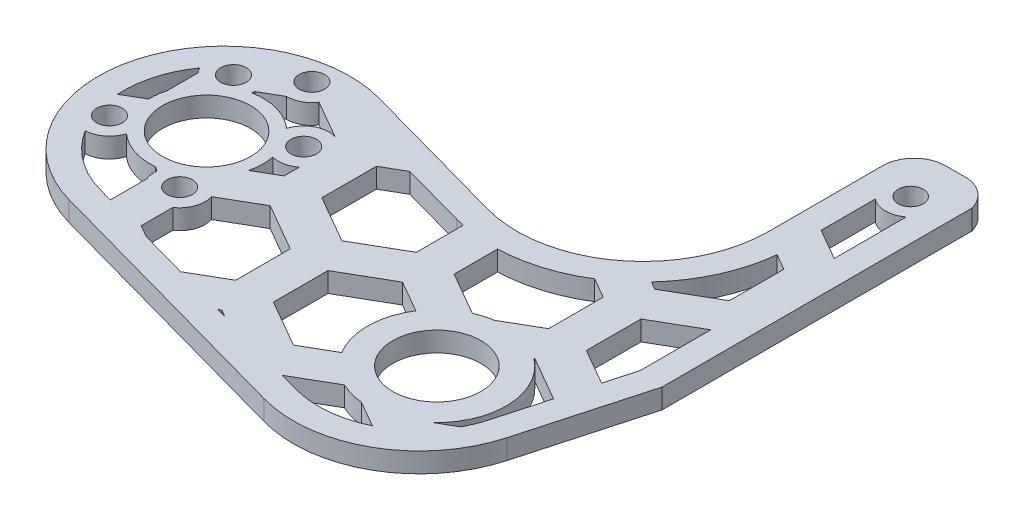
SolidWorks part; units mm, degrees
ref_plane "Front Plane" through (0, 0, 0) normal (0, 0, 1) x (1, 0, 0)
ref_plane "Top Plane" through (0, 0, 0) normal (0, 1, 0) x (1, 0, 0)
ref_plane "Right Plane" through (0, 0, 0) normal (1, 0, 0) x (0, 0, -1)
sketch "Sketch1" plane through (0, 0, 0) normal (0, 1, 0) x (1, 0, 0)
  line L12 (51.0281, 31.393) -> (48.107, 31.393)
  line L13 (43.107, 26.393) -> (43.107, 8.3528)
  line L14 (17.7622, -10.9198) -> (-6.126, -4.295)
  line L15 (-16.8156, -42.8402) -> (26.066, -54.7323)
  line L16 (50.6833, -40.8045) -> (56.0281, -21.5319)
  line L17 (56.0281, -21.5319) -> (56.0281, 26.393)
  circle A2 centre (35.2653, -36.5287) radius 7
  circle A4 centre (-15.3253, -22.4986) radius 7
  circle A6 centre (-5.4784, -16.9275) radius 2.025
  circle A8 centre (-9.7542, -32.3456) radius 2.025
  circle A10 centre (-25.1723, -28.0698) radius 2.025
  circle A12 centre (-20.8965, -12.6517) radius 2.025
  circle A14 centre (-13.7258, -7.3761) radius 2.025
  circle A16 centre (49.5676, 24.393) radius 2.05
  arc A28 (48.107, 31.393) -> (43.107, 26.393) centre (48.107, 26.393) ccw
  arc A29 (17.7622, -10.9198) -> (43.107, 8.3528) centre (23.107, 8.3528) ccw
  arc A30 (-6.126, -4.295) -> (-30.7434, -18.2228) centre (-11.4708, -23.5676) ccw
  arc A31 (-30.7434, -18.2228) -> (-16.8156, -42.8402) centre (-11.4708, -23.5676) ccw
  arc A32 (26.066, -54.7323) -> (50.6833, -40.8045) centre (31.4107, -35.4597) ccw
  arc A33 (56.0281, 26.393) -> (51.0281, 31.393) centre (51.0281, 26.393) ccw
extrude "Boss-Extrude1" add sketch "Sketch1" along normal blind 3.15
sketch "Sketch2" plane through (0, 3.15, 0) normal (0, 1, 0) x (1, 0, 0)
  line L0 (56.0281, -21.5319) -> (56.0281, 26.393) construction
  line L1 (0, 8.6603) -> (-7.5, 4.3301)
  line L2 (-7.5, 4.3301) -> (-7.5, -4.3301)
  line L3 (-7.5, -4.3301) -> (0, -8.6603)
  line L4 (0, -8.6603) -> (7.5, -4.3301)
  line L5 (7.5, -4.3301) -> (7.5, 4.3301)
  line L6 (7.5, 4.3301) -> (0, 8.6603)
  line L7 (21, 8.6603) -> (13.5, 4.3301)
  line L8 (13.5, 4.3301) -> (13.5, -4.3301)
  line L9 (13.5, -4.3301) -> (21, -8.6603)
  line L10 (21, -8.6603) -> (28.5, -4.3301)
  line L11 (28.5, -4.3301) -> (28.5, 4.3301)
  line L12 (28.5, 4.3301) -> (21, 8.6603)
  line L19 (10.5, -9.5263) -> (3, -13.8564)
  line L20 (3, -13.8564) -> (3, -22.5167)
  line L21 (3, -22.5167) -> (10.5, -26.8468)
  line L22 (10.5, -26.8468) -> (18, -22.5167)
  line L23 (18, -22.5167) -> (18, -13.8564)
  line L24 (18, -13.8564) -> (10.5, -9.5263)
  line L25 (31.5, -9.5263) -> (24, -13.8564)
  line L26 (24, -13.8564) -> (24, -22.5167)
  line L27 (24, -22.5167) -> (31.5, -26.8468)
  line L28 (31.5, -26.8468) -> (39, -22.5167)
  line L29 (39, -22.5167) -> (39, -13.8564)
  line L30 (39, -13.8564) -> (31.5, -9.5263)
  line L31 (10.5, -9.5263) -> (31.5, -9.5263) construction
  line L32 (52.5, -9.5263) -> (45, -13.8564)
  line L33 (45, -13.8564) -> (45, -22.5167)
  line L34 (45, -22.5167) -> (52.5, -26.8468)
  line L35 (52.5, -26.8468) -> (60, -22.5167)
  line L36 (60, -22.5167) -> (60, -13.8564)
  line L37 (60, -13.8564) -> (52.5, -9.5263)
  line L38 (42, 8.6603) -> (34.5, 4.3301)
  line L39 (34.5, 4.3301) -> (34.5, -4.3301)
  line L40 (34.5, -4.3301) -> (42, -8.6603)
  line L41 (42, -8.6603) -> (49.5, -4.3301)
  line L42 (49.5, -4.3301) -> (49.5, 4.3301)
  line L43 (49.5, 4.3301) -> (42, 8.6603)
  line L44 (63, 8.6603) -> (55.5, 4.3301)
  line L45 (55.5, 4.3301) -> (55.5, -4.3301)
  line L46 (55.5, -4.3301) -> (63, -8.6603)
  line L47 (63, -8.6603) -> (70.5, -4.3301)
  line L48 (70.5, -4.3301) -> (70.5, 4.3301)
  line L49 (70.5, 4.3301) -> (63, 8.6603)
  line L50 (73.5, -9.5263) -> (66, -13.8564)
  line L51 (66, -13.8564) -> (66, -22.5167)
  line L52 (66, -22.5167) -> (73.5, -26.8468)
  line L53 (73.5, -26.8468) -> (81, -22.5167)
  line L54 (81, -22.5167) -> (81, -13.8564)
  line L55 (81, -13.8564) -> (73.5, -9.5263)
  line L56 (52.5, -45.8993) -> (45, -50.2295)
  line L57 (45, -50.2295) -> (45, -58.8897)
  line L58 (45, -58.8897) -> (52.5, -63.2199)
  line L59 (52.5, -63.2199) -> (60, -58.8897)
  line L60 (60, -58.8897) -> (60, -50.2295)
  line L61 (60, -50.2295) -> (52.5, -45.8993)
  line L62 (42, -27.7128) -> (34.5, -32.0429)
  line L63 (34.5, -32.0429) -> (34.5, -40.7032)
  line L64 (34.5, -40.7032) -> (42, -45.0333)
  line L65 (42, -45.0333) -> (49.5, -40.7032)
  line L66 (49.5, -40.7032) -> (49.5, -32.0429)
  line L67 (49.5, -32.0429) -> (42, -27.7128)
  line L68 (63, -27.7128) -> (55.5, -32.0429)
  line L69 (55.5, -32.0429) -> (55.5, -40.7032)
  line L70 (55.5, -40.7032) -> (63, -45.0333)
  line L71 (63, -45.0333) -> (70.5, -40.7032)
  line L72 (70.5, -40.7032) -> (70.5, -32.0429)
  line L73 (70.5, -32.0429) -> (63, -27.7128)
  line L74 (73.5, -45.8993) -> (66, -50.2295)
  line L75 (66, -50.2295) -> (66, -58.8897)
  line L76 (66, -58.8897) -> (73.5, -63.2199)
  line L77 (73.5, -63.2199) -> (81, -58.8897)
  line L78 (81, -58.8897) -> (81, -50.2295)
  line L79 (81, -50.2295) -> (73.5, -45.8993)
  line L80 (10.5, -45.8993) -> (3, -50.2295)
  line L81 (3, -50.2295) -> (3, -58.8897)
  line L82 (3, -58.8897) -> (10.5, -63.2199)
  line L83 (10.5, -63.2199) -> (18, -58.8897)
  line L84 (18, -58.8897) -> (18, -50.2295)
  line L85 (18, -50.2295) -> (10.5, -45.8993)
  line L86 (0, -27.7128) -> (-7.5, -32.0429)
  line L87 (-7.5, -32.0429) -> (-7.5, -40.7032)
  line L88 (-7.5, -40.7032) -> (0, -45.0333)
  line L89 (0, -45.0333) -> (7.5, -40.7032)
  line L90 (7.5, -40.7032) -> (7.5, -32.0429)
  line L91 (7.5, -32.0429) -> (0, -27.7128)
  line L92 (21, -27.7128) -> (13.5, -32.0429)
  line L93 (13.5, -32.0429) -> (13.5, -40.7032)
  line L94 (13.5, -40.7032) -> (21, -45.0333)
  line L95 (21, -45.0333) -> (28.5, -40.7032)
  line L96 (28.5, -40.7032) -> (28.5, -32.0429)
  line L97 (28.5, -32.0429) -> (21, -27.7128)
  line L98 (31.5, -45.8993) -> (24, -50.2295)
  line L99 (24, -50.2295) -> (24, -58.8897)
  line L100 (24, -58.8897) -> (31.5, -63.2199)
  line L101 (31.5, -63.2199) -> (39, -58.8897)
  line L102 (39, -58.8897) -> (39, -50.2295)
  line L103 (39, -50.2295) -> (31.5, -45.8993)
  line L104 (10.5, -9.5263) -> (52.5, -9.5263) construction
  line L105 (-21, -27.7128) -> (-28.5, -32.0429)
  line L106 (-28.5, -32.0429) -> (-28.5, -40.7032)
  line L107 (-28.5, -40.7032) -> (-21, -45.0333)
  line L108 (-21, -45.0333) -> (-13.5, -40.7032)
  line L109 (-13.5, -40.7032) -> (-13.5, -32.0429)
  line L110 (-13.5, -32.0429) -> (-21, -27.7128)
  line L111 (-10.5, -9.5263) -> (-18, -13.8564)
  line L112 (-18, -13.8564) -> (-18, -22.5167)
  line L113 (-18, -22.5167) -> (-10.5, -26.8468)
  line L114 (-10.5, -26.8468) -> (-3, -22.5167)
  line L115 (-3, -22.5167) -> (-3, -13.8564)
  line L116 (-3, -13.8564) -> (-10.5, -9.5263)
  line L117 (-21, 8.6603) -> (-28.5, 4.3301)
  line L118 (-28.5, 4.3301) -> (-28.5, -4.3301)
  line L119 (-28.5, -4.3301) -> (-21, -8.6603)
  line L120 (-21, -8.6603) -> (-13.5, -4.3301)
  line L121 (-13.5, -4.3301) -> (-13.5, 4.3301)
  line L122 (-13.5, 4.3301) -> (-21, 8.6603)
  line L123 (-10.5, -45.8993) -> (-18, -50.2295)
  line L124 (-18, -50.2295) -> (-18, -58.8897)
  line L125 (-18, -58.8897) -> (-10.5, -63.2199)
  line L126 (-10.5, -63.2199) -> (-3, -58.8897)
  line L127 (-3, -58.8897) -> (-3, -50.2295)
  line L128 (-3, -50.2295) -> (-10.5, -45.8993)
  line L129 (-42, -27.7128) -> (-49.5, -32.0429)
  line L130 (-49.5, -32.0429) -> (-49.5, -40.7032)
  line L131 (-49.5, -40.7032) -> (-42, -45.0333)
  line L132 (-42, -45.0333) -> (-34.5, -40.7032)
  line L133 (-34.5, -40.7032) -> (-34.5, -32.0429)
  line L134 (-34.5, -32.0429) -> (-42, -27.7128)
  line L135 (-31.5, -9.5263) -> (-39, -13.8564)
  line L136 (-39, -13.8564) -> (-39, -22.5167)
  line L137 (-39, -22.5167) -> (-31.5, -26.8468)
  line L138 (-31.5, -26.8468) -> (-24, -22.5167)
  line L139 (-24, -22.5167) -> (-24, -13.8564)
  line L140 (-24, -13.8564) -> (-31.5, -9.5263)
  line L141 (-42, 8.6603) -> (-49.5, 4.3301)
  line L142 (-49.5, 4.3301) -> (-49.5, -4.3301)
  line L143 (-49.5, -4.3301) -> (-42, -8.6603)
  line L144 (-42, -8.6603) -> (-34.5, -4.3301)
  line L145 (-34.5, -4.3301) -> (-34.5, 4.3301)
  line L146 (-34.5, 4.3301) -> (-42, 8.6603)
  line L147 (-31.5, -45.8993) -> (-39, -50.2295)
  line L148 (-39, -50.2295) -> (-39, -58.8897)
  line L149 (-39, -58.8897) -> (-31.5, -63.2199)
  line L150 (-31.5, -63.2199) -> (-24, -58.8897)
  line L151 (-24, -58.8897) -> (-24, -50.2295)
  line L152 (-24, -50.2295) -> (-31.5, -45.8993)
  line L153 (0, -27.7128) -> (-21, -27.7128) construction
  line L154 (42, 45.0333) -> (34.5, 40.7032)
  line L155 (34.5, 40.7032) -> (34.5, 32.0429)
  line L156 (34.5, 32.0429) -> (42, 27.7128)
  line L157 (42, 27.7128) -> (49.5, 32.0429)
  line L158 (49.5, 32.0429) -> (49.5, 40.7032)
  line L159 (49.5, 40.7032) -> (42, 45.0333)
  line L160 (63, 45.0333) -> (55.5, 40.7032)
  line L161 (55.5, 40.7032) -> (55.5, 32.0429)
  line L162 (55.5, 32.0429) -> (63, 27.7128)
  line L163 (63, 27.7128) -> (70.5, 32.0429)
  line L164 (70.5, 32.0429) -> (70.5, 40.7032)
  line L165 (70.5, 40.7032) -> (63, 45.0333)
  line L166 (73.5, 26.8468) -> (66, 22.5167)
  line L167 (66, 22.5167) -> (66, 13.8564)
  line L168 (66, 13.8564) -> (73.5, 9.5263)
  line L169 (73.5, 9.5263) -> (81, 13.8564)
  line L170 (81, 13.8564) -> (81, 22.5167)
  line L171 (81, 22.5167) -> (73.5, 26.8468)
  line L172 (52.5, 26.8468) -> (45, 22.5167)
  line L173 (45, 22.5167) -> (45, 13.8564)
  line L174 (45, 13.8564) -> (52.5, 9.5263)
  line L175 (52.5, 9.5263) -> (60, 13.8564)
  line L176 (60, 13.8564) -> (60, 22.5167)
  line L177 (60, 22.5167) -> (52.5, 26.8468)
  circle A0 centre (0, 0) radius 7.5 construction
  circle A1 centre (21, 0) radius 7.5 construction
  circle A2 centre (10.5, -18.1865) radius 7.5 construction
  dimension "D1" = 15
  dimension "D2" = 15
  dimension "D3" = 6
  dimension "D4" = 6
  dimension "D5" = 6
  dimension "D6" = 2
  dimension "D7" = 21
  dimension "D10" = 42
  dimension "D12" = 21
  dimension "D14" = 6
  dimension "D15" = 6
  dimension "D16" = 6
  dimension "D8" = 2
  dimension "D9" = 2
  dimension "D11" = 3
  dimension "D13" = 2
extrude "Cut-Extrude1" cut sketch "Sketch2" against normal blind 3.15
sketch "Sketch3" plane through (0, 3.15, 0) normal (0, 1, 0) x (1, 0, 0)
  line L0 (50.7938, 31.393) -> (48.107, 31.393)
  line L1 (43.107, 26.393) -> (43.107, 8.3528)
  line L2 (17.7622, -10.9198) -> (-6.126, -4.295)
  line L3 (-16.8156, -42.8402) -> (26.066, -54.7323)
  line L4 (50.6833, -40.8045) -> (56.0281, -21.5319)
  line L5 (56.0281, -21.5319) -> (56.0281, 27.6902)
  line L6 (17.7622, -10.9198) -> (3.1197, -6.8591) construction
  line L7 (43.107, 26.393) -> (43.107, 8.3528) construction
  line L8 (51.0281, 31.393) -> (48.3742, 31.393) construction
  line L9 (56.0281, 4.635) -> (56.0281, 11.5632) construction
  line L10 (50.6833, -40.8045) -> (54.9458, -25.4347) construction
  line L11 (18, -52.4954) -> (24, -54.1594) construction
  line L13 (47.107, 21.2393) -> (47.107, 8.3528)
  line L14 (16.6933, -14.7743) -> (-7.195, -8.1495)
  line L15 (-15.7466, -38.9857) -> (27.1349, -50.8778)
  line L16 (46.8288, -39.7355) -> (52.0281, -20.9875)
  line L17 (52.0281, -20.9875) -> (52.0281, 21.2393)
  line L18 (47.107, 26.393) -> (47.107, 8.3528) construction
  line L19 (52.0281, -20.9875) -> (52.0281, 26.9412) construction
  line L20 (50.9897, 27.393) -> (48.107, 27.393) construction
  line L21 (-9.7542, -32.3456) -> (-25.1723, -28.0698) construction
  line L22 (-9.7542, -32.3456) -> (-5.4784, -16.9275) construction
  line L23 (-25.1723, -28.0698) -> (-20.8965, -12.6517) construction
  line L24 (-5.4784, -16.9275) -> (-20.8965, -12.6517) construction
  line L25 (-9.7542, -32.3456) -> (-20.8965, -12.6517) construction
  line L26 (-25.1723, -28.0698) -> (-5.4784, -16.9275) construction
  arc A8 (48.107, 31.393) -> (43.107, 26.393) centre (48.107, 26.393) ccw
  arc A9 (17.7622, -10.9198) -> (43.107, 8.3528) centre (23.107, 8.3528) ccw
  arc A10 (-6.126, -4.295) -> (-30.2137, -16.5887) centre (-11.4708, -23.5676) ccw
  arc A11 (-30.2137, -16.5887) -> (-16.8156, -42.8402) centre (-11.4708, -23.5676) ccw
  arc A12 (26.066, -54.7323) -> (50.6833, -40.8045) centre (31.4107, -35.4597) ccw
  arc A13 (56.0281, 27.6902) -> (50.7938, 31.393) centre (51.1537, 26.3507) ccw
  arc A14 (31.7619, -9.6775) -> (37.1677, -5.8703) centre (23.107, 8.3528) ccw construction
  circle A15 centre (35.2653, -36.5287) radius 11
  arc A16 (43.6546, 28.6681) -> (43.107, 26.393) centre (48.107, 26.393) ccw construction
  arc A17 (39, -53.9638) -> (50.6833, -40.8045) centre (31.4107, -35.4597) ccw construction
  arc A19 (-17.074, -42.7667) -> (-16.8156, -42.8402) centre (-11.4708, -23.5676) ccw construction
  circle A20 centre (49.5676, 24.393) radius 2
  circle A21 centre (35.2653, -36.5287) radius 7
  circle A22 centre (-15.3253, -22.4986) radius 7
  circle A23 centre (-20.8965, -12.6517) radius 2.025
  circle A24 centre (-13.7258, -7.3761) radius 2.025
  circle A25 centre (-25.1723, -28.0698) radius 2.025
  circle A26 centre (-9.7542, -32.3456) radius 2.025
  arc A28 (16.6933, -14.7743) -> (47.107, 8.3528) centre (23.107, 8.3528) ccw
  arc A29 (-7.195, -8.1495) -> (-9.7112, -7.6647) centre (-11.4708, -23.5676) ccw
  arc A30 (-26.4651, -17.9845) -> (-27.4281, -24.7363) centre (-11.4708, -23.5676) ccw
  arc A31 (27.1349, -50.8778) -> (46.8288, -39.7355) centre (31.4107, -35.4597) ccw
  arc A33 (-17.5089, -8.7507) -> (-9.7112, -7.6647) centre (-13.7258, -7.3761) ccw
  arc A34 (-24.5469, -14.3472) -> (-22.0435, -16.5098) centre (-20.8965, -12.6517) ccw
  arc A35 (-25.0112, -32.0916) -> (-21.3142, -29.2168) centre (-25.1723, -28.0698) ccw
  arc A36 (-22.0435, -16.5098) -> (-24.1684, -24.172) centre (-15.3253, -22.4986) ccw
  arc A37 (-13.652, -31.3417) -> (-8.6072, -28.4875) centre (-9.7542, -32.3456) ccw
  circle A38 centre (35.2653, -36.5287) radius 9 construction
  arc A39 (47.107, 21.2393) -> (52.0281, 21.2393) centre (49.5676, 24.393) ccw
  circle A40 centre (-20.8965, -12.6517) radius 4.025 construction
  arc A41 (-24.5469, -14.3472) -> (-26.4651, -17.9845) centre (-11.4708, -23.5676) ccw
  arc A42 (-7.195, -8.1495) -> (-26.4651, -17.9845) centre (-11.4708, -23.5676) ccw construction
  circle A43 centre (-13.7258, -7.3761) radius 4.025 construction
  arc A44 (-17.5089, -8.7507) -> (-18.687, -9.2873) centre (-11.4708, -23.5676) ccw
  circle A45 centre (-15.3253, -22.4986) radius 9 construction
  arc A46 (-16.9987, -13.6556) -> (-18.687, -9.2873) centre (-20.8965, -12.6517) ccw
  circle A47 centre (-25.1723, -28.0698) radius 4.025 construction
  arc A48 (-24.1684, -24.172) -> (-27.4281, -24.7363) centre (-25.1723, -28.0698) ccw
  arc A49 (-26.4651, -17.9845) -> (-15.7466, -38.9857) centre (-11.4708, -23.5676) ccw construction
  arc A50 (-25.0112, -32.0916) -> (-15.7466, -38.9857) centre (-11.4708, -23.5676) ccw
  arc A51 (-21.3142, -29.2168) -> (-13.652, -31.3417) centre (-15.3253, -22.4986) ccw
  circle A52 centre (-9.7542, -32.3456) radius 4.025 construction
  arc A53 (-8.6072, -28.4875) -> (-6.4823, -20.8253) centre (-15.3253, -22.4986) ccw
  circle A54 centre (49.5676, 24.393) radius 4 construction
  arc A55 (52.0281, 26.9412) -> (50.9897, 27.393) centre (51.1537, 26.3507) ccw construction
  arc A56 (48.107, 27.393) -> (47.107, 26.393) centre (48.107, 26.393) ccw construction
  circle A57 centre (-5.4784, -16.9275) radius 2.025
  arc A58 (-6.4823, -20.8253) -> (-9.3365, -15.7805) centre (-5.4784, -16.9275) ccw
  circle A59 centre (-5.4784, -16.9275) radius 4.025 construction
  arc A60 (-9.3365, -15.7805) -> (-16.9987, -13.6556) centre (-15.3253, -22.4986) ccw
  dimension "D3" = 2
  dimension "D1" = 4
  dimension "D2" = 2
extrude "Boss-Extrude2" add sketch "Sketch3" against normal blind 3.15 contours L5 A13 L0 A8 L1 A9 L2 A10 A11 L3 A12 L4 A36 A48 A30 A41 A34 A20 A22 A23 A24 A25 A26 A37 A53 A46 A44 A33 A29 L14 A28 L13 A39 L17 L16 A31 L15 A50 A35 A51 | A38 A21
